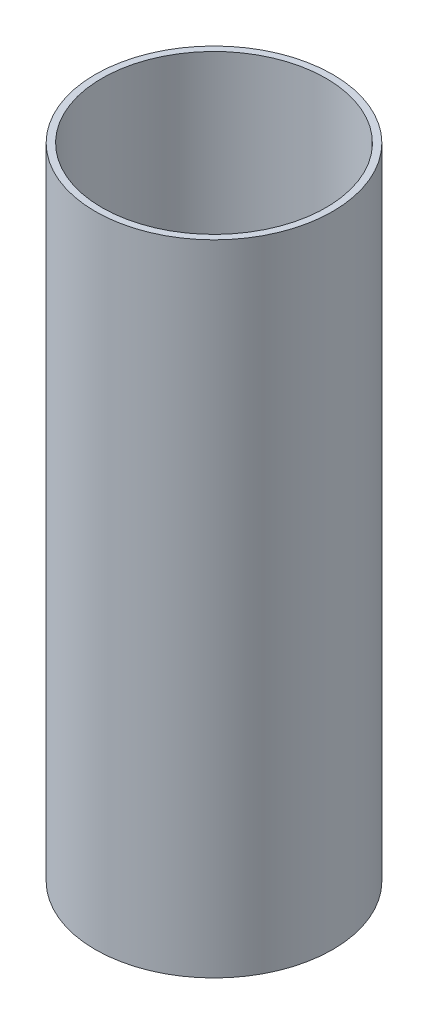
SolidWorks part; units mm, degrees
material "Rubber"
ref_plane "Front Plane" through (0, 0, 0) normal (0, 0, 1) x (1, 0, 0)
ref_plane "Top Plane" through (0, 0, 0) normal (0, 1, 0) x (1, 0, 0)
ref_plane "Right Plane" through (0, 0, 0) normal (1, 0, 0) x (0, 0, -1)
sketch "Sketch1" plane through (0, 0, 0) normal (0, 1, 0) x (1, 0, 0)
  circle A0 centre (0, 0) radius 6.135
  circle A1 centre (0, 0) radius 6.5
extrude "Boss-Extrude1" add sketch "Sketch1" along normal blind 35
